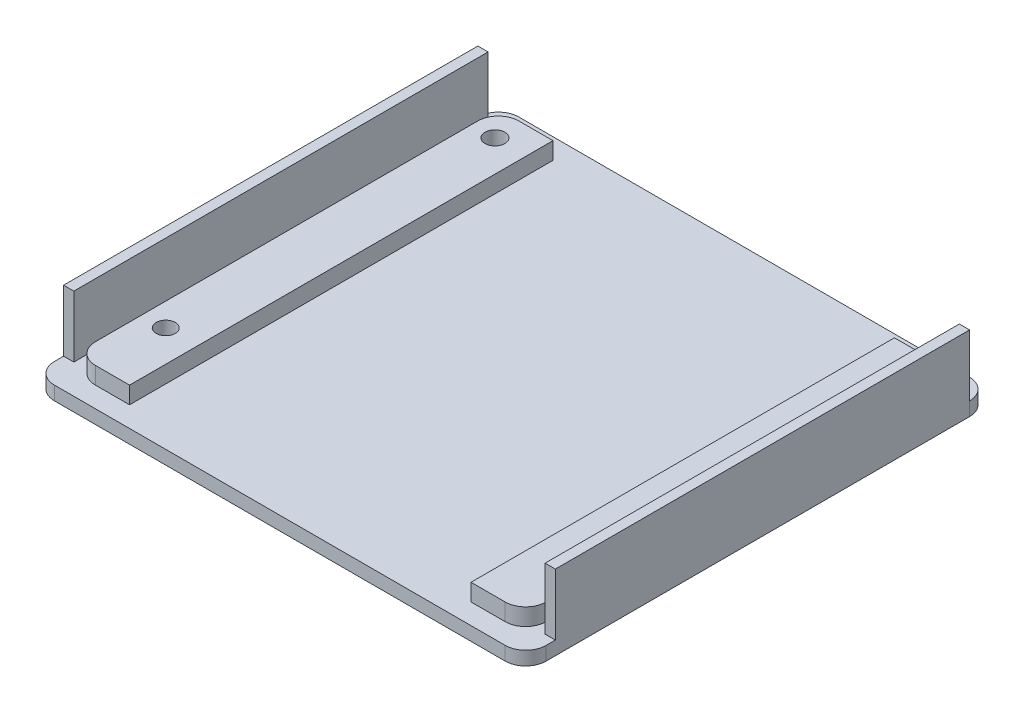
SolidWorks part; units mm, degrees
ref_plane "前视基准面" through (0, 0, 0) normal (0, 0, 1) x (1, 0, 0)
ref_plane "上视基准面" through (0, 0, 0) normal (0, 1, 0) x (1, 0, 0)
ref_plane "右视基准面" through (0, 0, 0) normal (1, 0, 0) x (0, 0, -1)
other "Configuration Table"
sketch "草图2" plane through (0, 0, 0) normal (0, 1, 0) x (1, 0, 0)
  line L1 (-33, 34) -> (33, 34)
  line L2 (-36, 31) -> (-36, -31)
  line L3 (-33, -34) -> (33, -34)
  line L4 (36, 31) -> (36, -31)
  line L5 (-36, 34) -> (36, -34) construction
  line L6 (-36, -34) -> (36, 34) construction
  arc A0 (-36, -31) -> (-33, -34) centre (-33, -31) ccw
  arc A1 (33, -34) -> (36, -31) centre (33, -31) ccw
  arc A2 (33, 34) -> (36, 31) centre (33, 31) cw
  arc A3 (-33, 34) -> (-36, 31) centre (-33, 31) ccw
  point P0 (0, 0)
  dimension "D3" = 3
  dimension "D1" = 68
  dimension "D2" = 72
extrude "凸台-拉伸1" add sketch "草图2" along normal blind 2
sketch "草图3" plane through (0, 2, 0) normal (0, 1, 0) x (1, 0, 0)
  line L0 (0, 0) -> (0, 28.5313) construction
  line L1 (-36, 31) -> (-34.5, 31)
  line L2 (-36, 31) -> (-36, -29.6598)
  line L3 (-36, -29.6598) -> (-34.5, -29.6598)
  line L4 (-34.5, 31) -> (-34.5, -29.6598)
  line L5 (36, -29.6598) -> (34.5, -29.6598)
  line L6 (34.5, 31) -> (34.5, -29.6598)
  line L7 (36, 31) -> (34.5, 31)
  line L8 (36, 31) -> (36, -29.6598)
  dimension "D1" = 1.5
extrude "凸台-拉伸2" add sketch "草图3" along normal blind 9
sketch "草图4" plane through (0, 2, 0) normal (0, 1, 0) x (1, 0, 0)
  line L0 (-34.5, -29.6598) -> (-34.5, 31) construction
  line L1 (-30, 31) -> (-25, 31)
  line L2 (-33, 28) -> (-33, -28)
  line L3 (-30, -31) -> (-25, -31)
  line L4 (-25, 31) -> (-25, -31)
  line L5 (33, 34) -> (-33, 34) construction
  line L6 (-33, -34) -> (33, -34) construction
  line L7 (0, 0) -> (0, 24.6653) construction
  line L8 (30, -31) -> (25, -31)
  line L9 (25, 31) -> (25, -31)
  line L10 (30, 31) -> (25, 31)
  line L11 (33, 28) -> (33, -28)
  circle A0 centre (-29.6, 27.1) radius 1.45
  circle A1 centre (-29.6, -21.1) radius 1.4
  arc A2 (-33, -28) -> (-30, -31) centre (-30, -28) ccw
  arc A3 (-30, 31) -> (-33, 28) centre (-30, 28) ccw
  arc A4 (33, -28) -> (30, -31) centre (30, -28) cw
  arc A5 (30, 31) -> (33, 28) centre (30, 28) cw
  circle A6 centre (29.6, 27.1) radius 1.45
  circle A7 centre (29.6, -21.1) radius 1.4
  dimension "D5" = 3.4
  dimension "D7" = 12.9
  dimension "D8" = 3
  dimension "D1" = 1.5
  dimension "D2" = 8
  dimension "D3" = 3
  dimension "D4" = 3
  dimension "D6" = 6.9
extrude "凸台-拉伸3" add sketch "草图4" along normal blind 2.5
